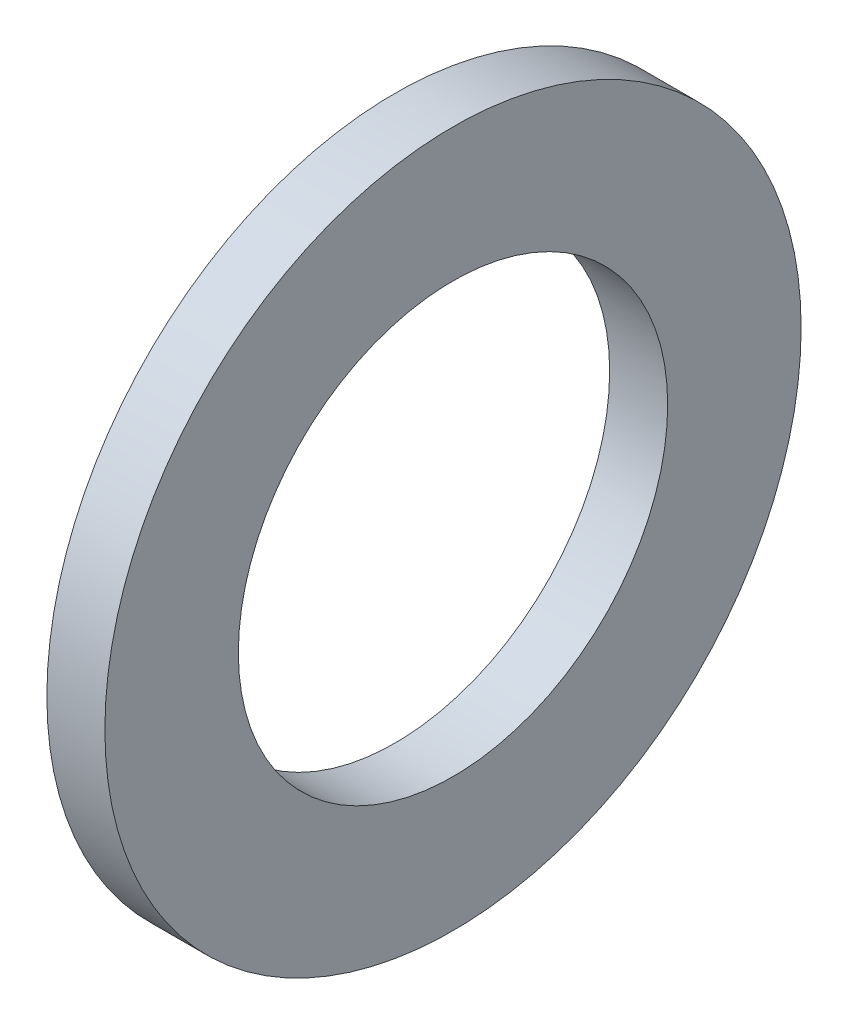
SolidWorks part; units mm, degrees
ref_plane "Plane1" through (0, 0, 0) normal (0, 0, 1) x (1, 0, 0)
ref_plane "Plane2" through (0, 0, 0) normal (0, 1, 0) x (1, 0, 0)
ref_plane "Plane3" through (0, 0, 0) normal (1, 0, 0) x (0, 0, -1)
sketch "Sketch1" plane through (0, 0, 0) normal (0, 0, 1) x (1, 0, 0)
  line L0 (-34.925, 0) -> (9.525, 0) construction
  line L1 (0, 18.5) -> (0, 30)
  line L2 (0, 30) -> (-5, 30)
  line L3 (-5, 30) -> (-5, 18.5)
  line L4 (-5, 18.5) -> (0, 18.5)
  dimension "Thickness" = 5
  dimension "Inside_dia" = 37
  dimension "Outside_dia" = 60
revolve "Base-Revolve" add sketch "Sketch1" angle 360 about L0
